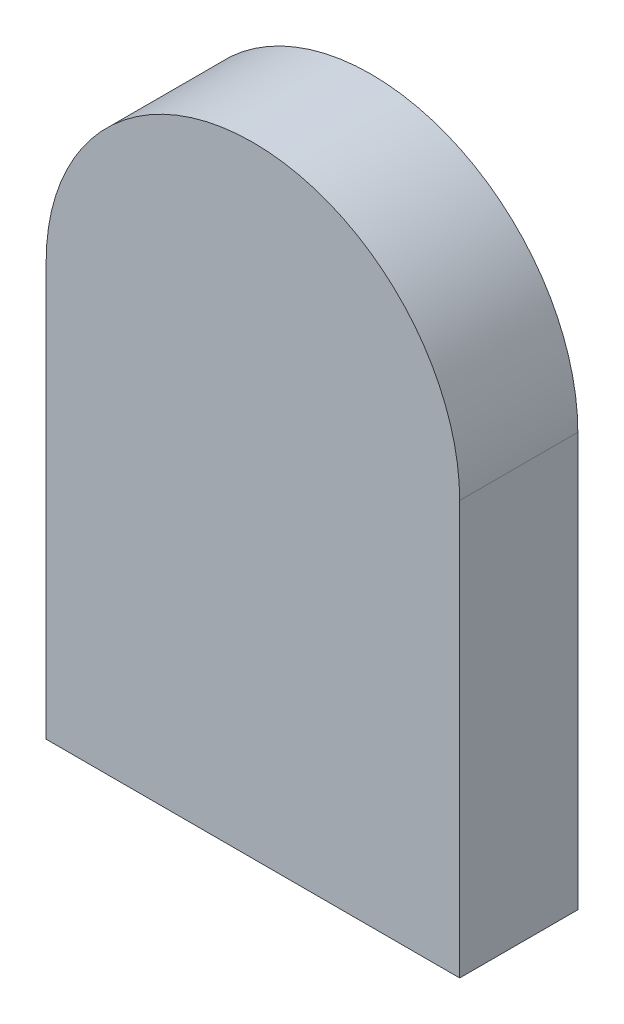
SolidWorks part; units mm, degrees
ref_plane "Front Plane" through (0, 0, 0) normal (0, 0, 1) x (1, 0, 0)
ref_plane "Top Plane" through (0, 0, 0) normal (0, 1, 0) x (1, 0, 0)
ref_plane "Right Plane" through (0, 0, 0) normal (1, 0, 0) x (0, 0, -1)
sketch "Sketch1" plane through (0, 0, 0) normal (0, 0, 1) x (1, 0, 0)
  line L0 (0, 0) -> (35, 0)
  line L1 (35, 0) -> (35, 35)
  line L3 (0, 35) -> (0, 0)
  arc A0 (0, 35) -> (35, 35) centre (17.5, 35) cw
  dimension "D1" = 35
  dimension "D2" = 35
extrude "Boss-Extrude1" add sketch "Sketch1" along normal blind 10
